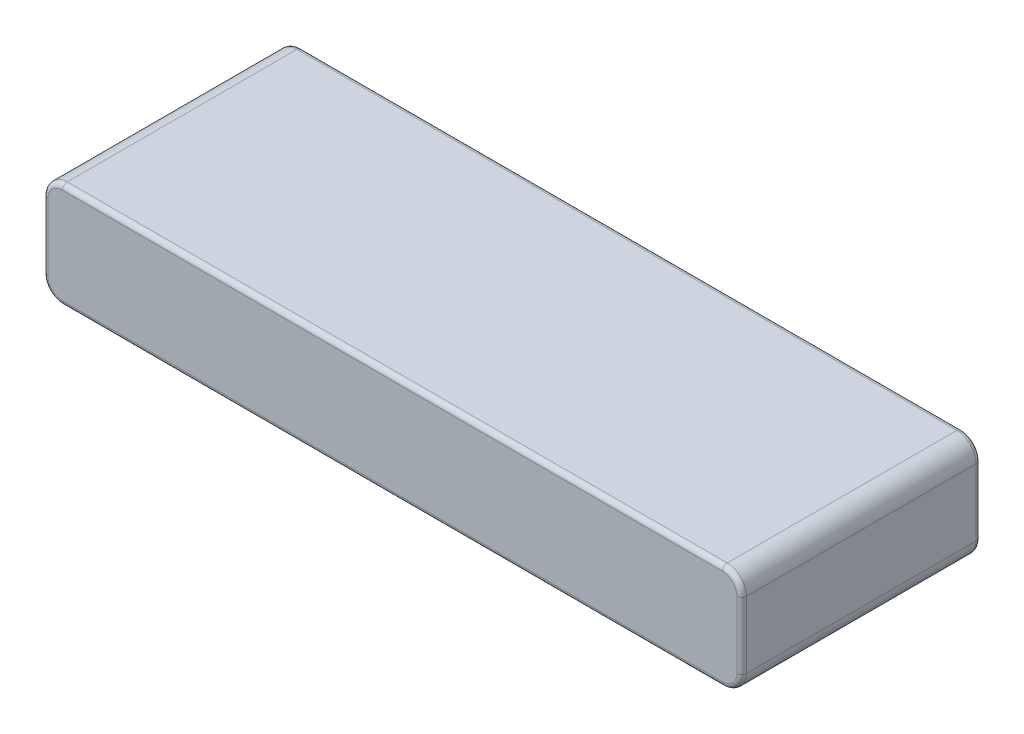
SolidWorks part; units mm, degrees
ref_plane "Front Plane" through (0, 0, 0) normal (0, 0, 1) x (1, 0, 0)
ref_plane "Top Plane" through (0, 0, 0) normal (0, 1, 0) x (1, 0, 0)
ref_plane "Right Plane" through (0, 0, 0) normal (1, 0, 0) x (0, 0, -1)
sketch "Sketch1" plane through (0, 0, 0) normal (0, 1, 0) x (1, 0, 0)
  line L1 (-72.4789, 24.8158) -> (72.4789, 24.8158)
  line L2 (-72.4789, 24.8158) -> (-72.4789, -24.8158)
  line L3 (-72.4789, -24.8158) -> (72.4789, -24.8158)
  line L4 (72.4789, 24.8158) -> (72.4789, -24.8158)
  line L5 (-72.4789, 24.8158) -> (72.4789, -24.8158) construction
  line L6 (-72.4789, -24.8158) -> (72.4789, 24.8158) construction
  point P0 (0, 0)
  dimension "D1" = 144.9578
  dimension "D2" = 49.6316
extrude "Boss-Extrude1" add sketch "Sketch1" along normal blind 21.8694
fillet "Fillet1" radius 4 4 edges at (72.4789, 0, 0) (72.4789, 21.8694, 0) (-72.4789, 0, 0) (-72.4789, 21.8694, 0)
fillet "Fillet2" radius 1 16 edges at (-71.3073, 20.6978, 24.8158) (-72.4789, 10.9347, 24.8158) (-71.3073, 1.1716, 24.8158) (0, 0, 24.8158) (71.3073, 1.1716, 24.8158) (72.4789, 10.9347, 24.8158) (71.3073, 20.6978, 24.8158) (71.3073, 20.6978, -24.8158) (72.4789, 10.9347, -24.8158) (71.3073, 1.1716, -24.8158) (0, 0, -24.8158) (-71.3073, 1.1716, -24.8158) (-72.4789, 10.9347, -24.8158) (-71.3073, 20.6978, -24.8158) (0, 21.8694, 24.8158) (0, 21.8694, -24.8158)
